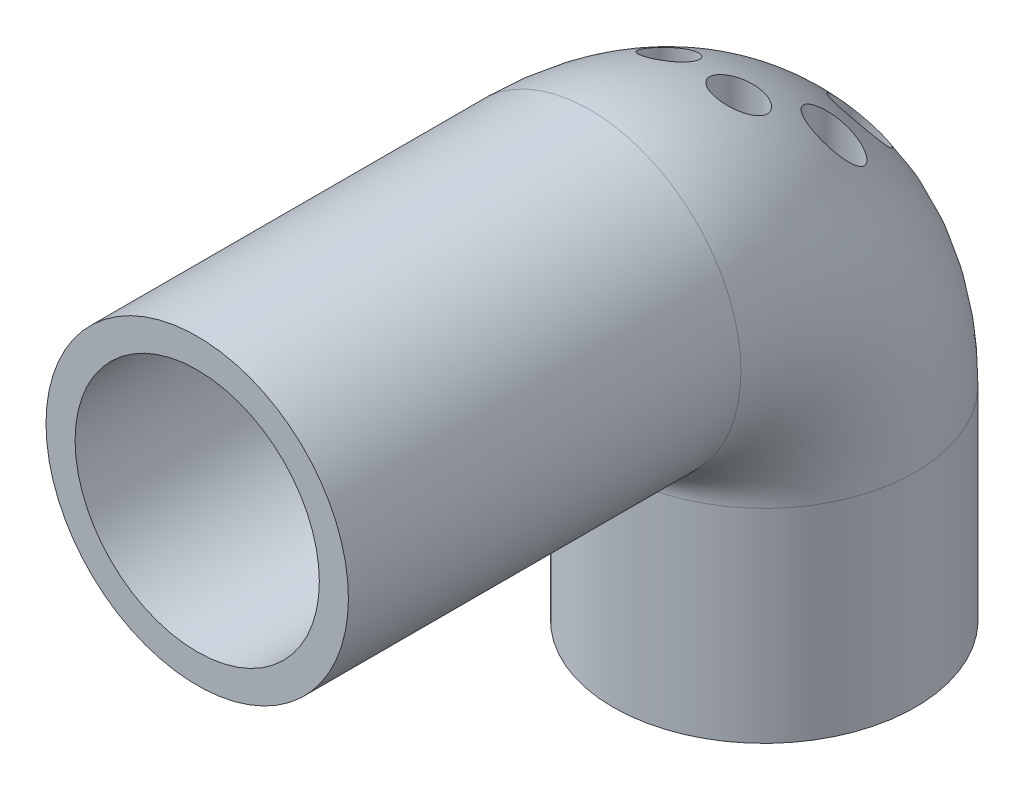
SolidWorks part; units mm, degrees
ref_plane "Front Plane" through (0, 0, 0) normal (0, 0, 1) x (1, 0, 0)
ref_plane "Top Plane" through (0, 0, 0) normal (0, 1, 0) x (1, 0, 0)
ref_plane "Right Plane" through (0, 0, 0) normal (1, 0, 0) x (0, 0, -1)
sketch "Sketch1" plane through (0, 0, 0) normal (0, 1, 0) x (1, 0, 0)
  line L0 (-21.2616, 0) -> (18.5116, 0) construction
  circle A1 centre (0, 0) radius 26
  dimension "D1" = 52
extrude "Boss-Extrude1" add sketch "Sketch1" along normal blind 5
sketch "Sketch8" plane through (0, 5, 0) normal (0, 1, 0) x (1, 0, 0)
  line L0 (6, 10.3923) -> (-6, -10.3923) construction
  line L2 (6, -10.3923) -> (-6, 10.3923) construction
  line L5 (0, 0) -> (0, 12) construction
  circle A0 centre (0, 0) radius 12 construction
  point P4 (-12, 0)
  point P6 (12, 0)
  point P9 (6, 10.3923)
  point P10 (-6, -10.3923)
  point P13 (6, -10.3923)
  point P14 (-6, 10.3923)
  dimension "D1" = 24
  dimension "D2" = 30
  dimension "D3" = 30
hole_wizard "CSK for M4 Flat Head Machine Screw2" positions "Sketch8" profile "Sketch9" countersink size "M4" standard "ANSI Metric" end condition through all
sketch "Sketch9" plane through (-6, 5, -10.3923) normal (1, 0, 0) x (0, 0, 1)
  line L0 (0, 0) -> (0, 5)
  line L1 (0, 5) -> (2.25, 5)
  line L2 (2.25, 5) -> (2.25, 1.75)
  line L3 (2.25, 1.75) -> (4, 0)
  line L5 (4, 0) -> (0, 0)
  line L6 (-2.25, 1.75) -> (-4, 0) construction
  line L11 (0, -6.35) -> (0, 107.95) construction
  dimension "Thru Hole Dia." = 4.5
  dimension "Thru Hole Depth" = 5
  dimension "Near C'Sink Dia." = 8
  dimension "Near C'Sink Angle" = 90
sketch "Sketch10" plane through (0, 0, 0) normal (1, 0, 0) x (0, 0, -1)
  line L0 (0, 5) -> (0, 35)
  line L1 (26, 5) -> (-26, 5) construction
  line L2 (-60, 65) -> (-30, 65)
  arc A0 (-30, 65) -> (0, 35) centre (-30, 35) cw
  dimension "D1" = 30
  dimension "D2" = 30
  dimension "D3" = 30
  dimension "D4" = 30
sketch "Sketch11" plane through (0, 5, 0) normal (0, 1, 0) x (1, 0, 0)
  circle A0 centre (0, 0) radius 21
  circle A1 centre (0, 0) radius 26
  circle A2 centre (0, 0) radius 26
  dimension "D1" = 0
  dimension "D2" = 5
sweep "Sweep3" add profiles "Sketch11" path "Sketch10"
ref_plane "Plane1" through (0, 39, 0) normal (0, -1, 0) x (-1, 0, 0)
sketch "Sketch13" plane through (0, 39, 0) normal (0, -1, 0) x (-1, 0, 0)
  circle A0 centre (-6, 10.3923) radius 2.25 construction
  circle A1 centre (-6, 10.3923) radius 2.25 construction
  circle A2 centre (6, 10.3923) radius 2.25 construction
  circle A3 centre (6, 10.3923) radius 2.25 construction
  circle A4 centre (12, 0) radius 2.25 construction
  circle A5 centre (12, 0) radius 2.25 construction
  circle A6 centre (6, -10.3923) radius 2.25 construction
  circle A7 centre (6, -10.3923) radius 2.25 construction
  circle A8 centre (-6, -10.3923) radius 2.25 construction
  circle A9 centre (-6, -10.3923) radius 2.25 construction
  circle A10 centre (-12, 0) radius 2.25 construction
  circle A11 centre (-12, 0) radius 2.25 construction
  circle A12 centre (6, 10.3923) radius 4
  circle A13 centre (-6, 10.3923) radius 4
  circle A14 centre (-12, 0) radius 4
  circle A15 centre (-6, -10.3923) radius 4
  circle A16 centre (6, -10.3923) radius 4
  circle A17 centre (12, 0) radius 4
  dimension "D1" = 8
extrude "Cut-Extrude1" cut sketch "Sketch13" against normal blind 100
sketch "Sketch14" plane through (0, 0, 0) normal (0, -1, 0) x (1, 0, 0)
  line L0 (0, 0) -> (0, 8.85) construction
  line L1 (0, 0) -> (-7.6643, -4.425) construction
  line L2 (0, 0) -> (7.6643, -4.425) construction
  circle A0 centre (0, 8.85) radius 2.9
  circle A1 centre (0, 0) radius 8.85 construction
  circle A2 centre (7.6643, -4.425) radius 2.9
  circle A3 centre (-7.6643, -4.425) radius 2.9
  dimension "D1" = 17.7
  dimension "D4" = 5.8
  dimension "D2" = 120
  dimension "D3" = 120
extrude "Cut-Extrude2" cut sketch "Sketch14" against normal blind 1
sketch "Sketch15" plane through (0, 0, 60) normal (0, 0, 1) x (1, 0, 0)
  circle A0 centre (0, 65) radius 21 construction
  circle A1 centre (0, 65) radius 26
  circle A2 centre (0, 65) radius 26
  circle A3 centre (0, 65) radius 21
  dimension "D1" = 0
extrude "Boss-Extrude2" add sketch "Sketch15" along normal blind 37.5
